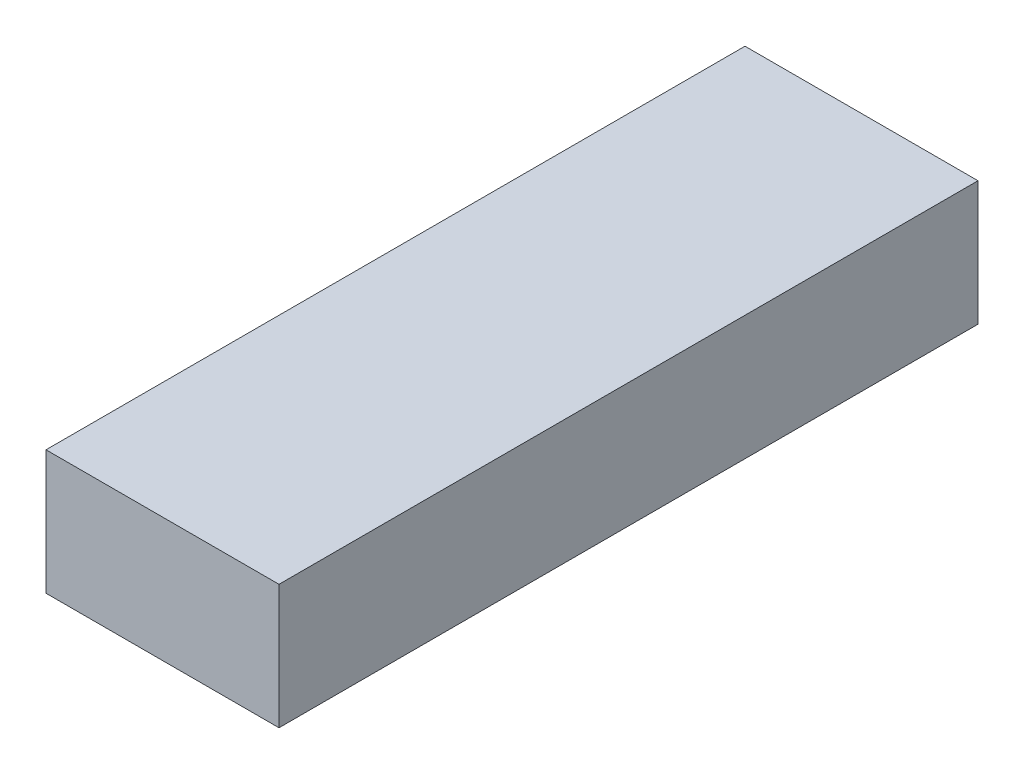
SolidWorks part; units mm, degrees
ref_plane "前视基准面" through (0, 0, 0) normal (0, 0, 1) x (1, 0, 0)
ref_plane "上视基准面" through (0, 0, 0) normal (0, 1, 0) x (1, 0, 0)
ref_plane "右视基准面" through (0, 0, 0) normal (1, 0, 0) x (0, 0, -1)
sketch "草图1" plane through (0, 0, 0) normal (0, 0, 1) x (1, 0, 0)
  line L1 (0, 0) -> (60, 0)
  line L2 (0, 0) -> (0, 32)
  line L3 (0, 32) -> (60, 32)
  line L4 (60, 0) -> (60, 32)
  dimension "D1" = 60
  dimension "D2" = 32
extrude "凸台-拉伸1" add sketch "草图1" along normal blind 180
sketch "草图2" plane through (0, 0, 0) normal (0, -1, 0) x (-1, 0, 0)
  line L0 (0, -180) -> (-60, -180) construction
  line L1 (-2, -178) -> (-58, -178)
  line L2 (-2, -178) -> (-2, -152)
  line L3 (-2, -152) -> (-58, -152)
  line L4 (-58, -178) -> (-58, -152)
  line L5 (0, -180) -> (0, 0) construction
  line L6 (-60, -180) -> (-60, 0) construction
  line L7 (-2, -148.5) -> (-58, -148.5)
  line L8 (-2, -148.5) -> (-2, -122.5)
  line L9 (-2, -122.5) -> (-58, -122.5)
  line L10 (-58, -148.5) -> (-58, -122.5)
  line L11 (-2, -119) -> (-58, -119)
  line L12 (-2, -119) -> (-2, -93)
  line L13 (-2, -93) -> (-58, -93)
  line L14 (-58, -119) -> (-58, -93)
  line L15 (-2, -89.5) -> (-58, -89.5)
  line L16 (-2, -89.5) -> (-2, -63.5)
  line L17 (-2, -63.5) -> (-58, -63.5)
  line L18 (-58, -89.5) -> (-58, -63.5)
  line L19 (-2, -60) -> (-58, -60)
  line L20 (-2, -60) -> (-2, -34)
  line L21 (-2, -34) -> (-58, -34)
  line L22 (-58, -60) -> (-58, -34)
  line L23 (-2, -30.5) -> (-58, -30.5)
  line L24 (-2, -30.5) -> (-2, -4.5)
  line L25 (-2, -4.5) -> (-58, -4.5)
  line L26 (-58, -30.5) -> (-58, -4.5)
  dimension "D1" = 2
  dimension "D2" = 2
  dimension "D3" = 2
  dimension "D4" = 26
  dimension "D5" = 6
extrude "切除-拉伸1" cut sketch "草图2" against normal blind 30
